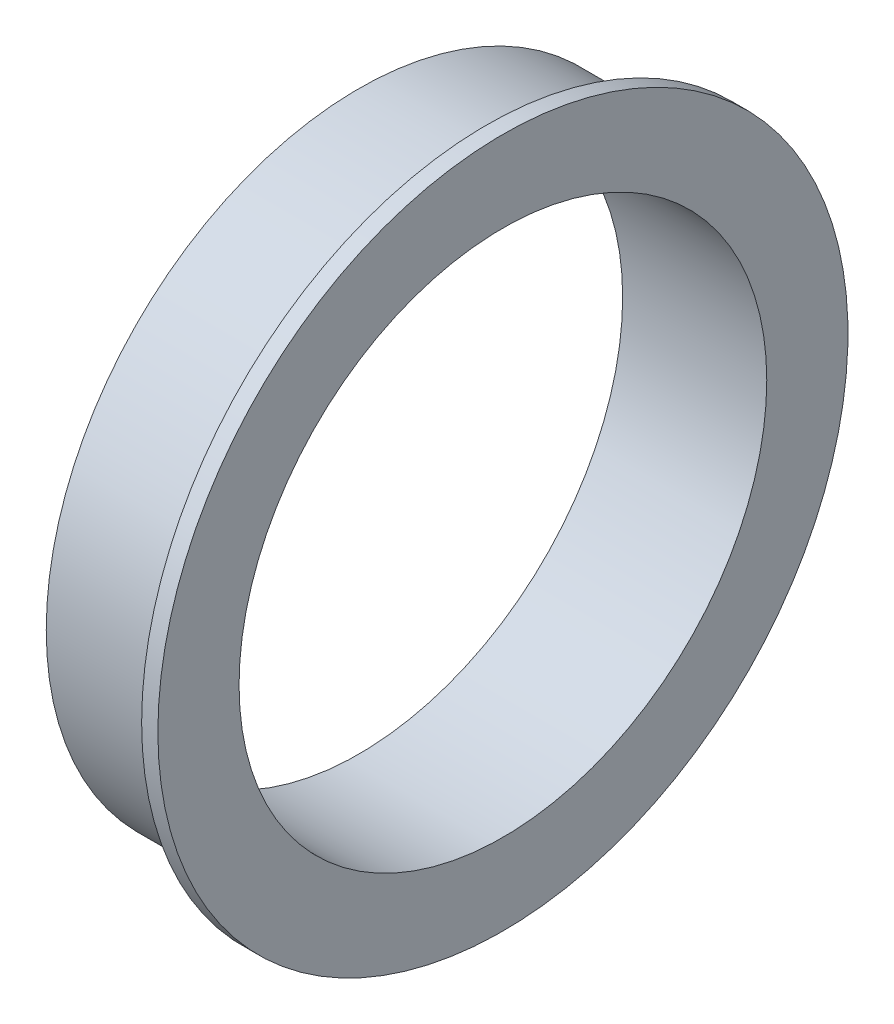
SolidWorks part; units mm, degrees
ref_plane "Piano frontale" through (0, 0, 0) normal (0, 0, 1) x (1, 0, 0)
ref_plane "Piano superiore" through (0, 0, 0) normal (0, 1, 0) x (1, 0, 0)
ref_plane "Piano destro" through (0, 0, 0) normal (1, 0, 0) x (0, 0, -1)
ref_axis "Axis2" through (-46.2, 0, 0) along (1, 0, 0)
sketch "Sketch3" plane through (0, 0, 0) normal (0, 0, 1) x (1, 0, 0)
  line L0 (14.9772, 77) -> (46.4772, 77)
  line L2 (46.4772, 77) -> (46.4772, 85)
  line L3 (46.4772, 85) -> (50.4772, 85)
  line L4 (50.4772, 85) -> (50.4772, 65)
  line L5 (50.4772, 65) -> (14.9772, 65)
  line L6 (14.9772, 65) -> (14.9772, 77)
  line L7 (-46.2, 0) -> (46.2, 0) construction
  dimension "D1" = 4
  dimension "D2" = 65
  dimension "D3" = 8
  dimension "D4" = 31.5
  dimension "D5" = 77
revolve "Boccola" add sketch "Sketch3" angle 360 about axis through (-46.2, 0, 0) along (1, 0, 0)
